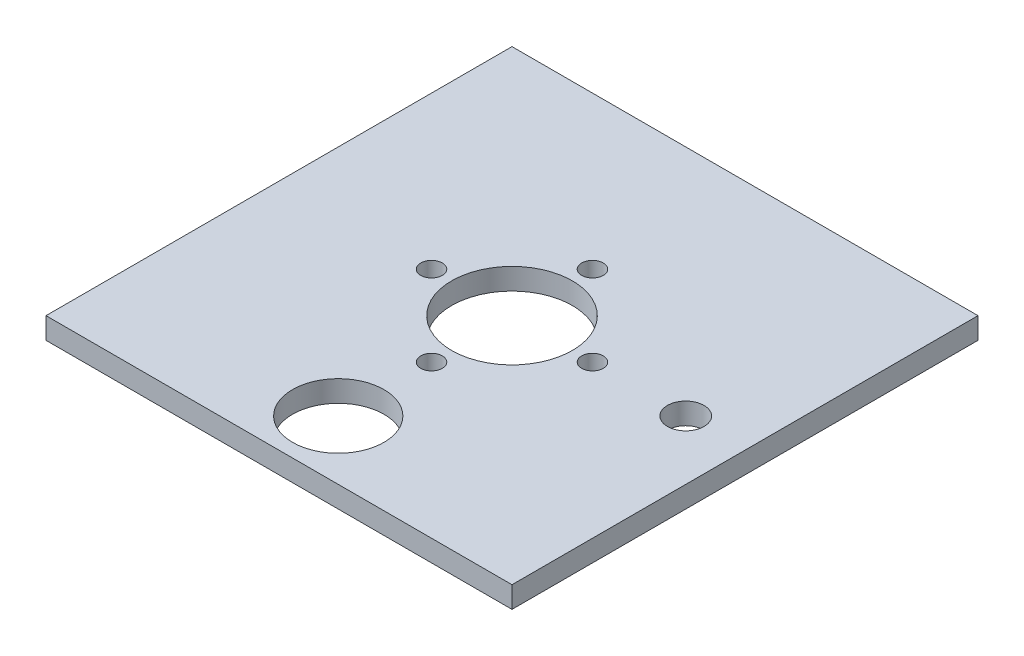
SolidWorks part; units mm, degrees
ref_plane "Front Plane" through (0, 0, 0) normal (0, 0, 1) x (1, 0, 0)
ref_plane "Top Plane" through (0, 0, 0) normal (0, 1, 0) x (1, 0, 0)
ref_plane "Right Plane" through (0, 0, 0) normal (1, 0, 0) x (0, 0, -1)
sketch "Sketch1" plane through (0, 0, 0) normal (0, 1, 0) x (1, 0, 0)
  line L0 (0, -32.3596) -> (0, 32.3596) construction
  line L1 (-32.3596, -32.3596) -> (32.3596, -32.3596)
  line L2 (-32.3596, -32.3596) -> (-32.3596, 32.3596)
  line L3 (-32.3596, 32.3596) -> (32.3596, 32.3596)
  line L4 (32.3596, -32.3596) -> (32.3596, 32.3596)
  line L5 (-32.3596, -32.3596) -> (32.3596, 32.3596) construction
  line L6 (-32.3596, 32.3596) -> (32.3596, -32.3596) construction
  line L7 (-32.3596, 0) -> (32.3596, 0) construction
  circle A0 centre (0, 0) radius 13.9446 construction
  circle A1 centre (24.13, 0) radius 2.54
  circle A2 centre (0, -24.13) radius 6.35
  circle A3 centre (0, 0) radius 8.382
  circle A4 centre (0, 11.176) radius 1.5
  circle A5 centre (11.176, 0) radius 1.5
  circle A6 centre (0, -11.176) radius 1.5
  circle A7 centre (-11.176, 0) radius 1.5
  point P7 (24.13, 0)
  point P10 (0, -24.13)
  point P14 (0, 11.176)
  point P17 (0, 0)
  point P20 (0, 0)
  point P32 (0, 0)
  dimension "D1" = 27.8892
  dimension "D5" = 5.08
  dimension "D7" = 12.7
  dimension "D8" = 16.764
  dimension "D10" = 3
  dimension "D2" = 32.3596
  dimension "D3" = 32.3596
  dimension "D4" = 24.13
  dimension "D6" = 24.13
  dimension "D9" = 11.176
  dimension "D11" = 4
extrude "Boss-Extrude1" add sketch "Sketch1" along normal blind 2.9718
